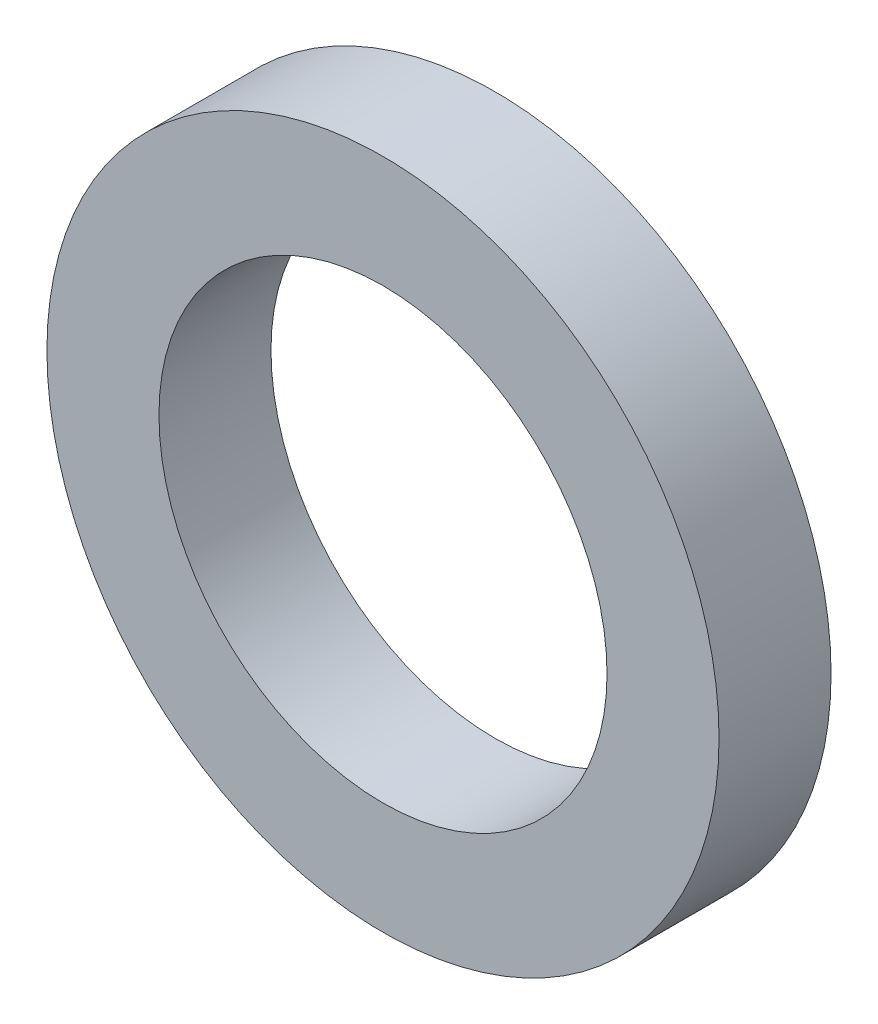
SolidWorks part; units mm, degrees
material "Silicon Rubber"
ref_plane "Front Plane" through (0, 0, 0) normal (0, 0, 1) x (1, 0, 0)
ref_plane "Top Plane" through (0, 0, 0) normal (0, 1, 0) x (1, 0, 0)
ref_plane "Right Plane" through (0, 0, 0) normal (1, 0, 0) x (0, 0, -1)
sketch "Sketch1" plane through (0, 0, 0) normal (0, 0, 1) x (1, 0, 0)
  circle A0 centre (0, 0) radius 19.05
  circle A1 centre (0, 0) radius 12.7
  dimension "D1" = 38.1
  dimension "D2" = 25.4
extrude "Boss-Extrude1" add sketch "Sketch1" along normal blind 6.35
